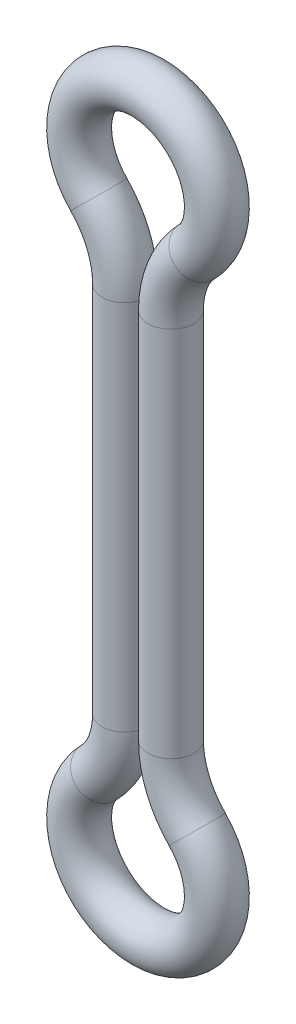
SolidWorks part; units mm, degrees
ref_plane "Front Plane" through (0, 0, 0) normal (0, 0, 1) x (1, 0, 0)
ref_plane "Top Plane" through (0, 0, 0) normal (0, 1, 0) x (1, 0, 0)
ref_plane "Right Plane" through (0, 0, 0) normal (1, 0, 0) x (0, 0, -1)
sketch "Sketch1" plane through (0, 0, 0) normal (0, 0, 1) x (1, 0, 0)
  line L0 (4, 9.798) -> (4, 42.202)
  line L2 (0, 42.202) -> (0, 9.798)
  line L3 (0, -55) -> (0, 55) construction
  line L4 (55, 0) -> (-55, 0) construction
  arc A0 (6.2857, 47.8009) -> (-2.2857, 47.8009) centre (2, 52) ccw
  arc A1 (-2.2857, 4.1991) -> (6.2857, 4.1991) centre (2, 0) ccw
  arc A2 (6.2857, 4.1991) -> (4, 9.798) centre (12, 9.798) cw
  arc A3 (-2.2857, 4.1991) -> (0, 9.798) centre (-8, 9.798) ccw
  arc A4 (4, 42.202) -> (6.2857, 47.8009) centre (12, 42.202) cw
  arc A5 (0, 42.202) -> (-2.2857, 47.8009) centre (-8, 42.202) ccw
  point P17 (4, 46.3431)
  point P20 (0, 46.3431)
  dimension "D3" = 64
  dimension "D4" = 12
  dimension "D5" = 6
  dimension "D6" = 8
  dimension "D1" = 4
  dimension "D2" = 2
ref_plane "Plane1" through (0, 10, 0) normal (0, 1, 0) x (-1, 0, 0)
sketch "Sketch2" plane through (0, 10, 0) normal (0, 1, 0) x (-1, 0, 0)
  circle A0 centre (0, 0) radius 2
  dimension "D1" = 4
sweep "Sweep1" add profiles "Sketch2" path "Sketch1"
